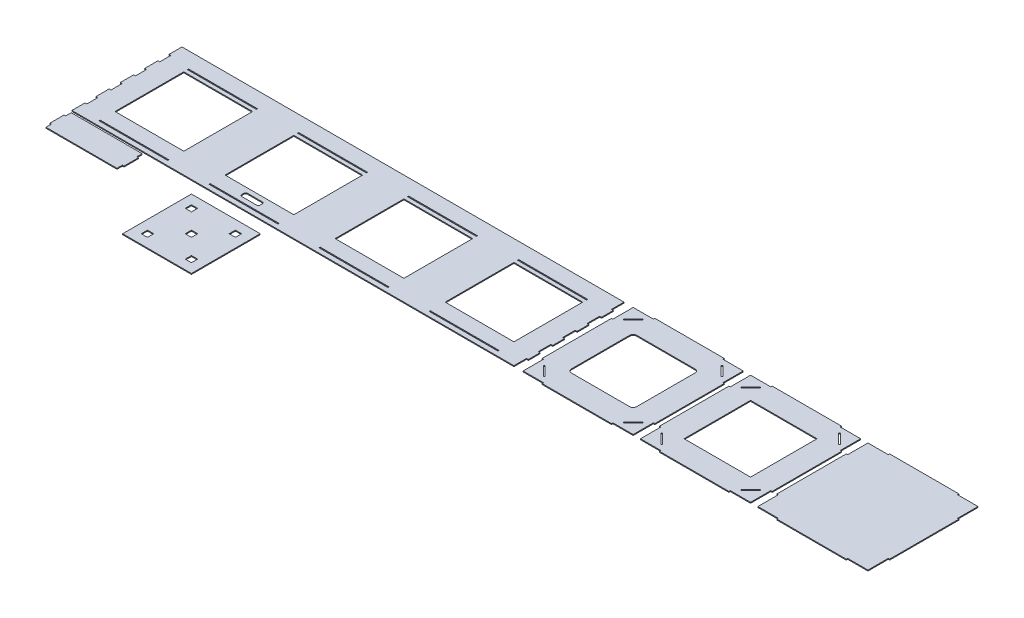
SolidWorks part; units mm, degrees
ref_plane "Front" through (0, 0, 0) normal (0, 0, 1) x (1, 0, 0)
ref_plane "Top" through (0, 0, 0) normal (0, 1, 0) x (1, 0, 0)
ref_plane "Right" through (0, 0, 0) normal (1, 0, 0) x (0, 0, -1)
sketch "Sketch1" plane through (0, 0, 0) normal (0, 1, 0) x (1, 0, 0)
  line L0 (0, 0) -> (457.2, 0) construction
  line L2 (-152.4, 152.4) -> (-152.4, -152.4) construction
  line L4 (152.4, 152.4) -> (152.4, -152.4) construction
  line L5 (-152.4, 152.4) -> (152.4, -152.4) construction
  line L6 (-152.4, -152.4) -> (152.4, 152.4) construction
  line L11 (152.4, 152.4) -> (457.2, 152.4)
  line L12 (152.4, 152.4) -> (152.4, -152.4) construction
  line L13 (152.4, -152.4) -> (457.2, -152.4)
  line L14 (457.2, 152.4) -> (457.2, -152.4) construction
  line L19 (-152.4, -152.4) -> (-457.2, -152.4)
  line L20 (-152.4, -152.4) -> (-152.4, 152.4) construction
  line L21 (-152.4, 152.4) -> (-457.2, 152.4)
  line L28 (152.4, -152.4) -> (-152.4, -152.4)
  line L34 (152.4, 152.4) -> (-152.4, 152.4)
  line L35 (-457.2, 152.4) -> (-457.2, -152.4) construction
  line L43 (-457.2, 152.4) -> (-762, 152.4)
  line L44 (-762, 152.4) -> (-762, -152.4) construction
  line L45 (-762, -152.4) -> (-457.2, -152.4)
  line L46 (457.2, 152.4) -> (457.2, 117.5512)
  line L47 (457.2, 117.5512) -> (462.28, 117.5512)
  line L48 (462.28, 117.5512) -> (462.28, 84.9122)
  line L49 (462.28, 84.9122) -> (457.2, 84.9122)
  line L50 (457.2, 84.9122) -> (457.2, 50.0634)
  line L51 (457.2, 50.0634) -> (462.28, 50.0634)
  line L63 (462.28, 50.0634) -> (462.28, 17.4244)
  line L64 (462.28, 17.4244) -> (457.2, 17.4244)
  line L65 (457.2, 17.4244) -> (457.2, -17.4244)
  line L66 (457.2, -17.4244) -> (462.28, -17.4244)
  line L67 (462.28, -17.4244) -> (462.28, -50.0634)
  line L68 (462.28, -50.0634) -> (457.2, -50.0634)
  line L69 (457.2, -50.0634) -> (457.2, -84.9122)
  line L70 (457.2, -84.9122) -> (462.28, -84.9122)
  line L71 (462.28, -84.9122) -> (462.28, -117.5512)
  line L72 (462.28, -117.5512) -> (457.2, -117.5512)
  line L73 (457.2, -117.5512) -> (457.2, -152.4)
  line L74 (-762, 152.4) -> (-767.08, 152.4)
  line L76 (-767.08, 116.4717) -> (-762, 116.4717)
  line L78 (-762, 85.9917) -> (-767.08, 85.9917)
  line L80 (-767.08, 48.9839) -> (-762, 48.9839)
  line L82 (-762, 18.5039) -> (-767.08, 18.5039)
  line L84 (-767.08, -18.5039) -> (-762, -18.5039)
  line L86 (-762, -48.9839) -> (-767.08, -48.9839)
  line L88 (-767.08, -85.9917) -> (-762, -85.9917)
  line L90 (-762, -116.4717) -> (-767.08, -116.4717)
  line L92 (-767.08, -152.4) -> (-762, -152.4)
  line L93 (462.28, 33.7439) -> (-762, 33.7439) construction
  line L94 (-762, 101.2317) -> (462.28, 101.2317) construction
  line L95 (-767.08, 152.4) -> (-767.08, 116.4717)
  line L96 (-767.08, 85.9917) -> (-767.08, 48.9839)
  line L97 (-762, 116.4717) -> (-762, 85.9917)
  line L98 (-762, 48.9839) -> (-762, 18.5039)
  line L99 (-762, -18.5039) -> (-762, -48.9839)
  line L100 (-762, -85.9917) -> (-762, -116.4717)
  line L101 (-762, -101.2317) -> (462.28, -101.2317) construction
  line L102 (-762, -33.7439) -> (462.28, -33.7439) construction
  line L103 (-767.08, 18.5039) -> (-767.08, -18.5039)
  line L104 (-767.08, -48.9839) -> (-767.08, -85.9917)
  line L105 (-767.08, -116.4717) -> (-767.08, -152.4)
  point P0 (0, 0)
  dimension "D1" = 304.8
  dimension "D2" = 304.8
  dimension "D3" = 5.08
  dimension "D4" = 32.639
  dimension "D5" = 30.48
extrude "Boss-Extrude1" add sketch "Sketch1" along normal blind 2.54
sketch "Sketch4" plane through (0, 2.54, 0) normal (0, 1, 0) x (1, 0, 0)
  line L0 (-457.2, 152.4) -> (-457.2, -152.4) construction
  line L1 (-457.2, 152.4) -> (-457.2, -152.4)
  line L2 (-152.4, 152.4) -> (-152.4, -152.4) construction
  line L3 (-152.4, 152.4) -> (-152.4, -152.4)
  line L4 (152.4, 152.4) -> (152.4, -152.4) construction
  line L5 (152.4, 152.4) -> (152.4, -152.4)
sketch "Sketch5" plane through (0, 2.54, 0) normal (0, 1, 0) x (1, 0, 0)
  line L0 (-762, -18.5039) -> (-762, 18.5039) construction
  line L1 (-457.2, 0) -> (-762, 0) construction
  line L2 (-457.2, 152.4) -> (-457.2, -152.4) construction
  line L3 (-457.2, 0) -> (-152.4, 0) construction
  line L4 (-152.4, 152.4) -> (-152.4, -152.4) construction
  line L5 (-152.4, 0) -> (152.4, 0) construction
  line L6 (152.4, 152.4) -> (152.4, -152.4) construction
  line L7 (152.4, 0) -> (457.2, 0) construction
  line L8 (457.2, -17.4244) -> (457.2, 17.4244) construction
  line L9 (-609.6, 0) -> (-609.6, -152.4) construction
  line L10 (-767.08, -152.4) -> (457.2, -152.4) construction
  line L11 (-304.8, 0) -> (-304.8, -152.4) construction
  line L12 (0, 0) -> (0, -152.4) construction
  line L13 (304.8, 0) -> (304.8, -152.4) construction
  line L14 (-514.35, -139.7) -> (-514.35, -152.4) construction
  line L15 (-704.85, -136.398) -> (-514.35, -136.398)
  line L16 (-704.85, -136.398) -> (-704.85, -139.7)
  line L17 (-704.85, -139.7) -> (-514.35, -139.7)
  line L18 (-514.35, -136.398) -> (-514.35, -139.7)
  line L19 (-704.85, -136.398) -> (-514.35, -139.7) construction
  line L20 (-704.85, -139.7) -> (-514.35, -136.398) construction
  line L21 (-400.05, -136.398) -> (-209.55, -136.398)
  line L22 (-400.05, -136.398) -> (-400.05, -139.7)
  line L23 (-400.05, -139.7) -> (-209.55, -139.7)
  line L24 (-209.55, -136.398) -> (-209.55, -139.7)
  line L25 (-400.05, -136.398) -> (-209.55, -139.7) construction
  line L26 (-400.05, -139.7) -> (-209.55, -136.398) construction
  line L27 (-95.25, -139.7) -> (95.25, -139.7)
  line L28 (-95.25, -139.7) -> (-95.25, -136.398)
  line L29 (-95.25, -136.398) -> (95.25, -136.398)
  line L30 (95.25, -139.7) -> (95.25, -136.398)
  line L31 (-95.25, -139.7) -> (95.25, -136.398) construction
  line L32 (-95.25, -136.398) -> (95.25, -139.7) construction
  line L33 (209.55, -139.7) -> (400.05, -139.7)
  line L34 (209.55, -139.7) -> (209.55, -136.398)
  line L35 (209.55, -136.398) -> (400.05, -136.398)
  line L36 (400.05, -139.7) -> (400.05, -136.398)
  line L37 (209.55, -139.7) -> (400.05, -136.398) construction
  line L38 (209.55, -136.398) -> (400.05, -139.7) construction
  line L39 (209.55, 136.398) -> (400.05, 139.7) construction
  line L40 (209.55, 139.7) -> (400.05, 136.398) construction
  line L41 (-95.25, 136.398) -> (95.25, 139.7) construction
  line L42 (-95.25, 139.7) -> (95.25, 136.398) construction
  line L43 (-400.05, 139.7) -> (-209.55, 136.398) construction
  line L44 (-400.05, 136.398) -> (-209.55, 139.7) construction
  line L45 (-704.85, 139.7) -> (-514.35, 136.398) construction
  line L46 (-704.85, 136.398) -> (-514.35, 139.7) construction
  line L47 (-609.6, 0) -> (-609.6, 107.061) construction
  line L48 (400.05, 139.7) -> (400.05, 136.398) construction
  line L49 (209.55, 136.398) -> (400.05, 136.398) construction
  line L50 (209.55, 139.7) -> (209.55, 136.398) construction
  line L51 (209.55, 139.7) -> (400.05, 139.7) construction
  line L52 (95.25, 139.7) -> (95.25, 136.398) construction
  line L53 (-95.25, 136.398) -> (95.25, 136.398) construction
  line L54 (-95.25, 139.7) -> (-95.25, 136.398) construction
  line L55 (-95.25, 139.7) -> (95.25, 139.7) construction
  line L56 (-209.55, 136.398) -> (-209.55, 139.7) construction
  line L57 (-400.05, 139.7) -> (-209.55, 139.7) construction
  line L58 (-400.05, 136.398) -> (-400.05, 139.7) construction
  line L59 (-400.05, 136.398) -> (-209.55, 136.398) construction
  line L60 (-514.35, 136.398) -> (-514.35, 139.7) construction
  line L61 (-704.85, 139.7) -> (-514.35, 139.7) construction
  line L62 (-704.85, 136.398) -> (-704.85, 139.7) construction
  line L63 (-704.85, 136.398) -> (-514.35, 136.398) construction
  line L64 (-304.8, 0) -> (-304.8, 107.061) construction
  line L65 (-704.85, 95.25) -> (-514.35, 95.25)
  line L66 (-704.85, 95.25) -> (-704.85, -95.25)
  line L67 (-704.85, -95.25) -> (-514.35, -95.25)
  line L68 (-514.35, 95.25) -> (-514.35, -95.25)
  line L69 (-704.85, 95.25) -> (-514.35, -95.25) construction
  line L70 (-704.85, -95.25) -> (-514.35, 95.25) construction
  line L71 (-400.05, 95.25) -> (-209.55, 95.25)
  line L72 (-400.05, 95.25) -> (-400.05, -95.25)
  line L73 (-400.05, -95.25) -> (-209.55, -95.25)
  line L74 (-209.55, 95.25) -> (-209.55, -95.25)
  line L75 (-400.05, 95.25) -> (-209.55, -95.25) construction
  line L76 (-400.05, -95.25) -> (-209.55, 95.25) construction
  line L77 (-95.25, 95.25) -> (95.25, 95.25)
  line L78 (-95.25, 95.25) -> (-95.25, -95.25)
  line L79 (-95.25, -95.25) -> (95.25, -95.25)
  line L80 (95.25, 95.25) -> (95.25, -95.25)
  line L81 (-95.25, 95.25) -> (95.25, -95.25) construction
  line L82 (-95.25, -95.25) -> (95.25, 95.25) construction
  line L83 (209.55, 95.25) -> (400.05, 95.25)
  line L84 (209.55, 95.25) -> (209.55, -95.25)
  line L85 (209.55, -95.25) -> (400.05, -95.25)
  line L86 (400.05, 95.25) -> (400.05, -95.25)
  line L87 (209.55, 95.25) -> (400.05, -95.25) construction
  line L88 (209.55, -95.25) -> (400.05, 95.25) construction
  line L89 (0, 0) -> (0, 107.061) construction
  line L90 (304.8, 0) -> (304.8, 107.061) construction
  line L91 (-400.05, -95.25) -> (-400.05, -136.398) construction
  line L92 (-704.85, 108.712) -> (-514.35, 108.712)
  line L93 (-704.85, 108.712) -> (-704.85, 105.41)
  line L94 (-704.85, 105.41) -> (-514.35, 105.41)
  line L95 (-514.35, 108.712) -> (-514.35, 105.41)
  line L96 (-704.85, 108.712) -> (-514.35, 105.41) construction
  line L97 (-704.85, 105.41) -> (-514.35, 108.712) construction
  line L98 (-400.05, 108.712) -> (-209.55, 108.712)
  line L99 (-400.05, 108.712) -> (-400.05, 105.41)
  line L100 (-400.05, 105.41) -> (-209.55, 105.41)
  line L101 (-209.55, 108.712) -> (-209.55, 105.41)
  line L102 (-400.05, 108.712) -> (-209.55, 105.41) construction
  line L103 (-400.05, 105.41) -> (-209.55, 108.712) construction
  line L104 (-95.25, 108.712) -> (95.25, 108.712)
  line L105 (-95.25, 108.712) -> (-95.25, 105.41)
  line L106 (-95.25, 105.41) -> (95.25, 105.41)
  line L107 (95.25, 108.712) -> (95.25, 105.41)
  line L108 (-95.25, 108.712) -> (95.25, 105.41) construction
  line L109 (-95.25, 105.41) -> (95.25, 108.712) construction
  line L110 (209.55, 108.712) -> (400.05, 108.712)
  line L111 (209.55, 108.712) -> (209.55, 105.41)
  line L112 (209.55, 105.41) -> (400.05, 105.41)
  line L113 (400.05, 108.712) -> (400.05, 105.41)
  line L114 (209.55, 108.712) -> (400.05, 105.41) construction
  line L115 (209.55, 105.41) -> (400.05, 108.712) construction
  line L116 (-209.55, -95.25) -> (-209.55, -136.398) construction
  line L117 (-209.55, -115.824) -> (-400.05, -115.824) construction
  line L119 (-325.12, -107.95) -> (-284.48, -107.95)
  line L120 (-330.2, -113.03) -> (-330.2, -118.618)
  line L121 (-325.12, -123.698) -> (-284.48, -123.698)
  line L122 (-279.4, -113.03) -> (-279.4, -118.618)
  line L123 (-330.2, -107.95) -> (-279.4, -123.698) construction
  line L124 (-330.2, -123.698) -> (-279.4, -107.95) construction
  arc A0 (-284.48, -107.95) -> (-279.4, -113.03) centre (-284.48, -113.03) cw
  arc A1 (-279.4, -118.618) -> (-284.48, -123.698) centre (-284.48, -118.618) cw
  arc A2 (-325.12, -123.698) -> (-330.2, -118.618) centre (-325.12, -118.618) cw
  arc A3 (-330.2, -113.03) -> (-325.12, -107.95) centre (-325.12, -113.03) cw
  point P27 (-609.6, -138.049)
  point P32 (-304.8, -138.049)
  point P37 (0, -138.049)
  point P42 (304.8, -138.049)
  point P66 (304.8, 138.049)
  point P67 (0, 138.049)
  point P68 (-304.8, 138.049)
  point P69 (-609.6, 138.049)
  point P106 (-304.8, -115.824)
  point P111 (-291.4538, -123.698)
  point P112 (0, 0)
  point P113 (0, 0)
  dimension "D5" = 10.16
  dimension "D7" = 12.7
  dimension "D9" = 5.08
  dimension "D1" = 12.7
  dimension "D2" = 3.302
  dimension "D3" = 190.5
  dimension "D4" = 190.5
  dimension "D6" = 12.7
  dimension "D8" = 50.8
extrude "Cut-Extrude2" cut sketch "Sketch5" against normal through all
sketch "Sketch6" plane through (0, 0, 0) normal (0, 1, 0) x (1, 0, 0)
  line L0 (0, 0) -> (635, 0) construction
  line L1 (635, 0) -> (635, 154.305) construction
  line L2 (482.6, 152.4) -> (787.4, 152.4) construction
  line L3 (482.6, 152.4) -> (482.6, -152.4) construction
  line L4 (482.6, -152.4) -> (787.4, -152.4) construction
  line L5 (787.4, 152.4) -> (787.4, -152.4) construction
  line L6 (482.6, 152.4) -> (787.4, -152.4) construction
  line L7 (482.6, -152.4) -> (787.4, 152.4) construction
  line L8 (635, 0) -> (789.305, 0) construction
  line L9 (635, 0) -> (635, -154.305) construction
  line L10 (482.6, 96.139) -> (482.6, 152.4)
  line L11 (538.861, 156.21) -> (731.139, 156.21)
  line L12 (538.861, 156.21) -> (538.861, 152.4)
  line L13 (538.861, 152.4) -> (731.139, 152.4) construction
  line L14 (731.139, 156.21) -> (731.139, 152.4)
  line L15 (538.861, 156.21) -> (731.139, 152.4) construction
  line L16 (538.861, 152.4) -> (731.139, 156.21) construction
  line L17 (791.21, -96.139) -> (787.4, -96.139)
  line L18 (791.21, -96.139) -> (791.21, 96.139)
  line L19 (791.21, 96.139) -> (787.4, 96.139)
  line L20 (787.4, -96.139) -> (787.4, 96.139) construction
  line L21 (791.21, -96.139) -> (787.4, 96.139) construction
  line L22 (791.21, 96.139) -> (787.4, -96.139) construction
  line L23 (538.861, -156.21) -> (731.139, -156.21)
  line L24 (538.861, -156.21) -> (538.861, -152.4)
  line L25 (538.861, -152.4) -> (731.139, -152.4) construction
  line L26 (731.139, -156.21) -> (731.139, -152.4)
  line L27 (538.861, -156.21) -> (731.139, -152.4) construction
  line L28 (538.861, -152.4) -> (731.139, -156.21) construction
  line L29 (478.79, 96.139) -> (482.6, 96.139)
  line L30 (478.79, 96.139) -> (478.79, -96.139)
  line L31 (478.79, -96.139) -> (482.6, -96.139)
  line L32 (482.6, 96.139) -> (482.6, -96.139) construction
  line L33 (478.79, 96.139) -> (482.6, -96.139) construction
  line L34 (478.79, -96.139) -> (482.6, 96.139) construction
  line L35 (482.6, 152.4) -> (538.861, 152.4)
  line L36 (731.139, 152.4) -> (787.4, 152.4)
  line L37 (787.4, 152.4) -> (787.4, 96.139)
  line L38 (787.4, -96.139) -> (787.4, -152.4)
  line L39 (787.4, -152.4) -> (731.139, -152.4)
  line L40 (538.861, -152.4) -> (482.6, -152.4)
  line L41 (482.6, -152.4) -> (482.6, -96.139)
  line L42 (803.91, 96.139) -> (803.91, -96.139)
  line L43 (803.91, 96.139) -> (807.72, 96.139)
  line L44 (807.72, 96.139) -> (807.72, 152.4)
  line L45 (807.72, 152.4) -> (863.981, 152.4)
  line L46 (863.981, 156.21) -> (863.981, 152.4)
  line L47 (863.981, 156.21) -> (1056.259, 156.21)
  line L48 (1056.259, 156.21) -> (1056.259, 152.4)
  line L49 (1056.259, 152.4) -> (1112.52, 152.4)
  line L50 (1112.52, 152.4) -> (1112.52, 96.139)
  line L51 (1116.33, 96.139) -> (1112.52, 96.139)
  line L52 (1116.33, -96.139) -> (1116.33, 96.139)
  line L53 (1116.33, -96.139) -> (1112.52, -96.139)
  line L54 (1112.52, -96.139) -> (1112.52, -152.4)
  line L55 (1112.52, -152.4) -> (1056.259, -152.4)
  line L56 (1056.259, -156.21) -> (1056.259, -152.4)
  line L57 (863.981, -156.21) -> (1056.259, -156.21)
  line L58 (863.981, -156.21) -> (863.981, -152.4)
  line L59 (863.981, -152.4) -> (807.72, -152.4)
  line L60 (807.72, -152.4) -> (807.72, -96.139)
  line L61 (803.91, -96.139) -> (807.72, -96.139)
  line L62 (807.72, 152.4) -> (1112.52, -152.4) construction
  line L63 (1129.03, 96.139) -> (1129.03, -96.139)
  line L64 (1129.03, 96.139) -> (1132.84, 96.139)
  line L65 (1132.84, 96.139) -> (1132.84, 152.4)
  line L66 (1132.84, 152.4) -> (1189.101, 152.4)
  line L67 (1189.101, 156.21) -> (1189.101, 152.4)
  line L68 (1189.101, 156.21) -> (1381.379, 156.21)
  line L69 (1381.379, 156.21) -> (1381.379, 152.4)
  line L70 (1381.379, 152.4) -> (1437.64, 152.4)
  line L71 (1437.64, 152.4) -> (1437.64, 96.139)
  line L72 (1441.45, 96.139) -> (1437.64, 96.139)
  line L73 (1441.45, -96.139) -> (1441.45, 96.139)
  line L74 (1441.45, -96.139) -> (1437.64, -96.139)
  line L75 (1437.64, -96.139) -> (1437.64, -152.4)
  line L76 (1437.64, -152.4) -> (1381.379, -152.4)
  line L77 (1381.379, -156.21) -> (1381.379, -152.4)
  line L78 (1189.101, -156.21) -> (1381.379, -156.21)
  line L79 (1189.101, -156.21) -> (1189.101, -152.4)
  line L80 (1189.101, -152.4) -> (1132.84, -152.4)
  line L81 (1132.84, -152.4) -> (1132.84, -96.139)
  line L82 (1129.03, -96.139) -> (1132.84, -96.139)
  line L84 (868.045, 92.075) -> (1052.195, 92.075)
  line L85 (868.045, 92.075) -> (868.045, -92.075)
  line L86 (868.045, -92.075) -> (1052.195, -92.075)
  line L87 (1052.195, 92.075) -> (1052.195, -92.075)
  line L88 (868.045, 92.075) -> (1052.195, -92.075) construction
  line L89 (868.045, -92.075) -> (1052.195, 92.075) construction
  point P22 (480.695, 0)
  point P67 (960.12, 0)
  dimension "D1" = 304.8
  dimension "D2" = 304.8
  dimension "D3" = 3.81
  dimension "D4" = 192.278
  dimension "D5" = 635
  dimension "D7" = 12.7
  dimension "D8" = 184.15
  dimension "D6" = 3
extrude "Boss-Extrude2" add sketch "Sketch6" along normal blind 2.54 separate body
sketch "Sketch7" plane through (0, 0, 0) normal (0, 1, 0) x (1, 0, 0)
  line L0 (-704.85, 105.41) -> (-704.85, -91.186) construction
  line L1 (-762.635, -158.75) -> (-566.039, -158.75)
  line L2 (-762.635, -158.75) -> (-762.635, -173.99)
  line L3 (-762.635, -228.6) -> (-566.039, -228.6)
  line L4 (-566.039, -158.75) -> (-566.039, -173.99)
  line L5 (-762.635, -158.75) -> (-566.039, -228.6) construction
  line L6 (-762.635, -228.6) -> (-566.039, -158.75) construction
  line L7 (-704.85, 95.25) -> (-704.85, -95.25) construction
  line L8 (-704.85, -91.186) -> (-704.85, -95.25) construction
  line L9 (482.6, -96.139) -> (482.6, -152.4) construction
  line L10 (482.6, -152.4) -> (538.861, -152.4) construction
  line L12 (-762.635, -173.99) -> (-767.08, -173.99)
  line L13 (499.595, -108.4642) -> (526.5358, -135.405) construction
  line L14 (499.595, -108.4642) -> (497.2601, -110.7991) construction
  line L15 (497.2601, -110.7991) -> (524.2009, -137.7399) construction
  line L16 (526.5358, -135.405) -> (524.2009, -137.7399) construction
  line L17 (499.595, -108.4642) -> (524.2009, -137.7399) construction
  line L18 (497.2601, -110.7991) -> (526.5358, -135.405) construction
  line L19 (-767.08, -173.99) -> (-767.08, -213.36)
  line L20 (-767.08, -213.36) -> (-762.635, -213.36)
  line L21 (482.6, -96.139) -> (538.861, -152.4) construction
  line L22 (511.8979, -123.1021) -> (510.7305, -124.2695) construction
  line L23 (-762.635, -213.36) -> (-762.635, -228.6)
  line L24 (-566.039, -173.99) -> (-561.594, -173.99)
  line L25 (-561.594, -173.99) -> (-561.594, -213.36)
  line L26 (-561.594, -213.36) -> (-566.039, -213.36)
  line L27 (-566.039, -213.36) -> (-566.039, -228.6)
  line L28 (-767.08, -152.4) -> (457.2, -152.4) construction
  line L29 (-767.08, -116.4717) -> (-767.08, -152.4) construction
  point P0 (-664.337, -193.675)
  point P14 (511.8979, -123.1021)
  point P31 (0, 0)
  point P38 (-704.85, 105.41)
  dimension "D1" = 69.85
  dimension "D2" = 4.064
  dimension "D3" = 3.302
  dimension "D4" = 39.37
  dimension "D5" = 38.1
  dimension "D6" = 4.445
  dimension "D7" = 6.35
extrude "Boss-Extrude3" add sketch "Sketch7" along normal blind 2.54 separate body
sketch "Sketch8" plane through (0, 2.54, 0) normal (0, 1, 0) x (1, 0, 0)
  line L0 (497.2601, -110.7991) -> (524.2009, -137.7399) construction
  line L1 (526.5358, -135.405) -> (524.2009, -137.7399) construction
  line L2 (499.595, -108.4642) -> (526.5358, -135.405) construction
  line L3 (499.595, -108.4642) -> (497.2601, -110.7991) construction
  line L4 (497.2601, -110.7991) -> (524.2009, -137.7399)
  line L5 (526.5358, -135.405) -> (524.2009, -137.7399)
  line L6 (499.595, -108.4642) -> (526.5358, -135.405)
  line L7 (499.595, -108.4642) -> (497.2601, -110.7991)
  line L8 (482.6, 152.4) -> (787.4, -152.4) construction
  line L9 (526.5358, 135.405) -> (499.595, 108.4642)
  line L10 (526.5358, 135.405) -> (524.2009, 137.7399)
  line L11 (524.2009, 137.7399) -> (497.2601, 110.7991)
  line L12 (499.595, 108.4642) -> (497.2601, 110.7991)
  line L13 (770.405, 108.4642) -> (743.4642, 135.405)
  line L14 (770.405, 108.4642) -> (772.7399, 110.7991)
  line L15 (772.7399, 110.7991) -> (745.7991, 137.7399)
  line L16 (743.4642, 135.405) -> (745.7991, 137.7399)
  line L17 (743.4642, -135.405) -> (770.405, -108.4642)
  line L18 (743.4642, -135.405) -> (745.7991, -137.7399)
  line L19 (745.7991, -137.7399) -> (772.7399, -110.7991)
  line L20 (770.405, -108.4642) -> (772.7399, -110.7991)
  line L21 (807.72, -96.139) -> (863.981, -152.4) construction
  line L22 (822.3801, -110.7991) -> (824.715, -108.4642)
  line L23 (824.715, -108.4642) -> (851.6558, -135.405)
  line L24 (851.6558, -135.405) -> (849.3209, -137.7399)
  line L25 (835.8505, -124.2695) -> (838.1854, -121.9346) construction
  line L26 (822.3801, -110.7991) -> (849.3209, -137.7399)
  line L27 (807.72, 152.4) -> (1112.52, -152.4) construction
  line L28 (824.715, 108.4642) -> (822.3801, 110.7991)
  line L29 (849.3209, 137.7399) -> (822.3801, 110.7991)
  line L30 (849.3209, 137.7399) -> (851.6558, 135.405)
  line L31 (851.6558, 135.405) -> (824.715, 108.4642)
  line L32 (1068.5842, 135.405) -> (1070.9191, 137.7399)
  line L33 (1097.8599, 110.7991) -> (1070.9191, 137.7399)
  line L34 (1097.8599, 110.7991) -> (1095.525, 108.4642)
  line L35 (1095.525, 108.4642) -> (1068.5842, 135.405)
  line L36 (1095.525, -108.4642) -> (1097.8599, -110.7991)
  line L37 (1070.9191, -137.7399) -> (1097.8599, -110.7991)
  line L38 (1070.9191, -137.7399) -> (1068.5842, -135.405)
  line L39 (1068.5842, -135.405) -> (1095.525, -108.4642)
  circle A0 centre (635, 0) radius 20.7898 construction
  circle A1 centre (635, 0) radius 20.7898 construction
  circle A2 centre (635, 0) radius 20.7898 construction
  circle A3 centre (635, 0) radius 20.7898 construction
  circle A4 centre (960.12, 0) radius 130.2137 construction
  point P28 (635, 0)
  point P58 (960.12, 0)
  dimension "D1" = 4
  dimension "D2" = 4
extrude "Cut-Extrude3" cut sketch "Sketch8" against normal through all
sketch "Sketch9" plane through (0, 0, 0) normal (0, 1, 0) x (1, 0, 0)
  line L1 (-401.1088, -187.3154) -> (-210.6088, -187.3154)
  line L2 (-401.1088, -187.3154) -> (-401.1088, -377.8154)
  line L3 (-401.1088, -377.8154) -> (-210.6088, -377.8154)
  line L4 (-210.6088, -187.3154) -> (-210.6088, -377.8154)
  line L5 (-401.1088, -187.3154) -> (-210.6088, -377.8154) construction
  line L6 (-401.1088, -377.8154) -> (-210.6088, -187.3154) construction
  line L7 (-314.4948, -273.9294) -> (-297.2228, -273.9294)
  line L8 (-314.4948, -273.9294) -> (-314.4948, -291.2014)
  line L9 (-314.4948, -291.2014) -> (-297.2228, -291.2014)
  line L10 (-297.2228, -273.9294) -> (-297.2228, -291.2014)
  line L11 (-314.4948, -273.9294) -> (-297.2228, -291.2014) construction
  line L12 (-314.4948, -291.2014) -> (-297.2228, -273.9294) construction
  line L13 (-366.7576, -221.6667) -> (-244.9601, -221.6667) construction
  line L14 (-366.7576, -221.6667) -> (-366.7576, -343.4641) construction
  line L15 (-366.7576, -343.4641) -> (-244.9601, -343.4641) construction
  line L16 (-244.9601, -221.6667) -> (-244.9601, -343.4641) construction
  line L17 (-366.7576, -221.6667) -> (-244.9601, -343.4641) construction
  line L18 (-366.7576, -343.4641) -> (-244.9601, -221.6667) construction
  line L19 (-375.3936, -213.0307) -> (-358.1216, -213.0307)
  line L20 (-375.3936, -213.0307) -> (-375.3936, -230.3027)
  line L21 (-375.3936, -230.3027) -> (-358.1216, -230.3027)
  line L22 (-358.1216, -213.0307) -> (-358.1216, -230.3027)
  line L23 (-375.3936, -213.0307) -> (-358.1216, -230.3027) construction
  line L24 (-375.3936, -230.3027) -> (-358.1216, -213.0307) construction
  line L25 (-375.3936, -334.8281) -> (-358.1216, -334.8281)
  line L26 (-375.3936, -334.8281) -> (-375.3936, -352.1001)
  line L27 (-375.3936, -352.1001) -> (-358.1216, -352.1001)
  line L28 (-358.1216, -334.8281) -> (-358.1216, -352.1001)
  line L29 (-375.3936, -334.8281) -> (-358.1216, -352.1001) construction
  line L30 (-375.3936, -352.1001) -> (-358.1216, -334.8281) construction
  line L31 (-236.3241, -334.8281) -> (-253.5961, -334.8281)
  line L32 (-236.3241, -334.8281) -> (-236.3241, -352.1001)
  line L33 (-236.3241, -352.1001) -> (-253.5961, -352.1001)
  line L34 (-253.5961, -334.8281) -> (-253.5961, -352.1001)
  line L35 (-236.3241, -334.8281) -> (-253.5961, -352.1001) construction
  line L36 (-236.3241, -352.1001) -> (-253.5961, -334.8281) construction
  line L37 (-253.5961, -213.0307) -> (-236.3241, -213.0307)
  line L38 (-253.5961, -213.0307) -> (-253.5961, -230.3027)
  line L39 (-253.5961, -230.3027) -> (-236.3241, -230.3027)
  line L40 (-236.3241, -213.0307) -> (-236.3241, -230.3027)
  line L41 (-253.5961, -213.0307) -> (-236.3241, -230.3027) construction
  line L42 (-253.5961, -230.3027) -> (-236.3241, -213.0307) construction
  point P0 (-305.8588, -282.5654)
  point P5 (-305.8588, -282.5654)
  point P12 (-305.8588, -282.5654)
  dimension "D1" = 190.5
  dimension "D2" = 190.5
  dimension "D3" = 17.272
  dimension "D4" = 17.272
extrude "Boss-Extrude4" add sketch "Sketch9" along normal blind 2.54 separate body
sketch "Sketch10" plane through (0, 2.54, 0) normal (0, 1, 0) x (1, 0, 0)
  line L0 (-514.35, 95.25) -> (-704.85, 95.25) construction
  line L1 (-209.55, 95.25) -> (-400.05, 95.25) construction
  line L2 (95.25, 95.25) -> (-95.25, 95.25) construction
  line L3 (400.05, 95.25) -> (209.55, 95.25) construction
  line L4 (-599.44, 95.25) -> (-619.76, 95.25)
  line L5 (-294.64, 95.25) -> (-314.96, 95.25)
  line L6 (10.16, 95.25) -> (-10.16, 95.25)
  line L7 (314.96, 95.25) -> (294.64, 95.25)
  line L8 (-704.85, -90.805) -> (-514.35, -90.805)
  line L9 (-609.6, -90.805) -> (-609.6, -95.25) construction
  line L14 (-704.85, 95.25) -> (-704.85, -95.25) construction
  line L15 (-514.35, -95.25) -> (-514.35, 95.25) construction
  line L16 (-704.85, -95.25) -> (-514.35, -95.25) construction
  line L17 (-400.05, -90.805) -> (-209.55, -90.805)
  line L18 (-400.05, 95.25) -> (-400.05, -95.25) construction
  line L19 (-209.55, -95.25) -> (-209.55, 95.25) construction
  line L20 (-95.25, -90.805) -> (95.25, -90.805)
  line L21 (-95.25, 95.25) -> (-95.25, -95.25) construction
  line L22 (95.25, -95.25) -> (95.25, 95.25) construction
  line L23 (209.55, -90.805) -> (400.05, -90.805)
  line L24 (209.55, 95.25) -> (209.55, -95.25) construction
  line L25 (400.05, -95.25) -> (400.05, 95.25) construction
  line L26 (-561.594, -173.99) -> (-566.039, -173.99) construction
  arc A0 (-619.76, 95.25) -> (-599.44, 95.25) centre (-609.6, 95.25) ccw
  arc A1 (-314.96, 95.25) -> (-294.64, 95.25) centre (-304.8, 95.25) ccw
  arc A2 (-10.16, 95.25) -> (10.16, 95.25) centre (0, 95.25) ccw
  arc A3 (294.64, 95.25) -> (314.96, 95.25) centre (304.8, 95.25) ccw
  dimension "D1" = 20.32
sketch "Sketch14" plane through (0, 2.54, 0) normal (0, 1, 0) x (1, 0, 0)
  line L0 (482.6, 152.4) -> (787.4, -152.4) construction
  line L2 (554.0375, 90.4875) -> (715.9625, 90.4875)
  line L3 (544.5125, 80.9625) -> (544.5125, -80.9625)
  line L4 (554.0375, -90.4875) -> (715.9625, -90.4875)
  line L5 (725.4875, 80.9625) -> (725.4875, -80.9625)
  line L6 (544.5125, 90.4875) -> (725.4875, -90.4875) construction
  line L7 (544.5125, -90.4875) -> (725.4875, 90.4875) construction
  arc A0 (725.4875, 80.9625) -> (715.9625, 90.4875) centre (715.9625, 80.9625) ccw
  arc A1 (554.0375, 90.4875) -> (544.5125, 80.9625) centre (554.0375, 80.9625) ccw
  arc A2 (544.5125, -80.9625) -> (554.0375, -90.4875) centre (554.0375, -80.9625) ccw
  arc A3 (725.4875, -80.9625) -> (715.9625, -90.4875) centre (715.9625, -80.9625) cw
  point P4 (635, 0)
  dimension "D2" = 9.525
  dimension "D1" = 180.975
extrude "Cut-Extrude4" cut sketch "Sketch14" against normal through all
